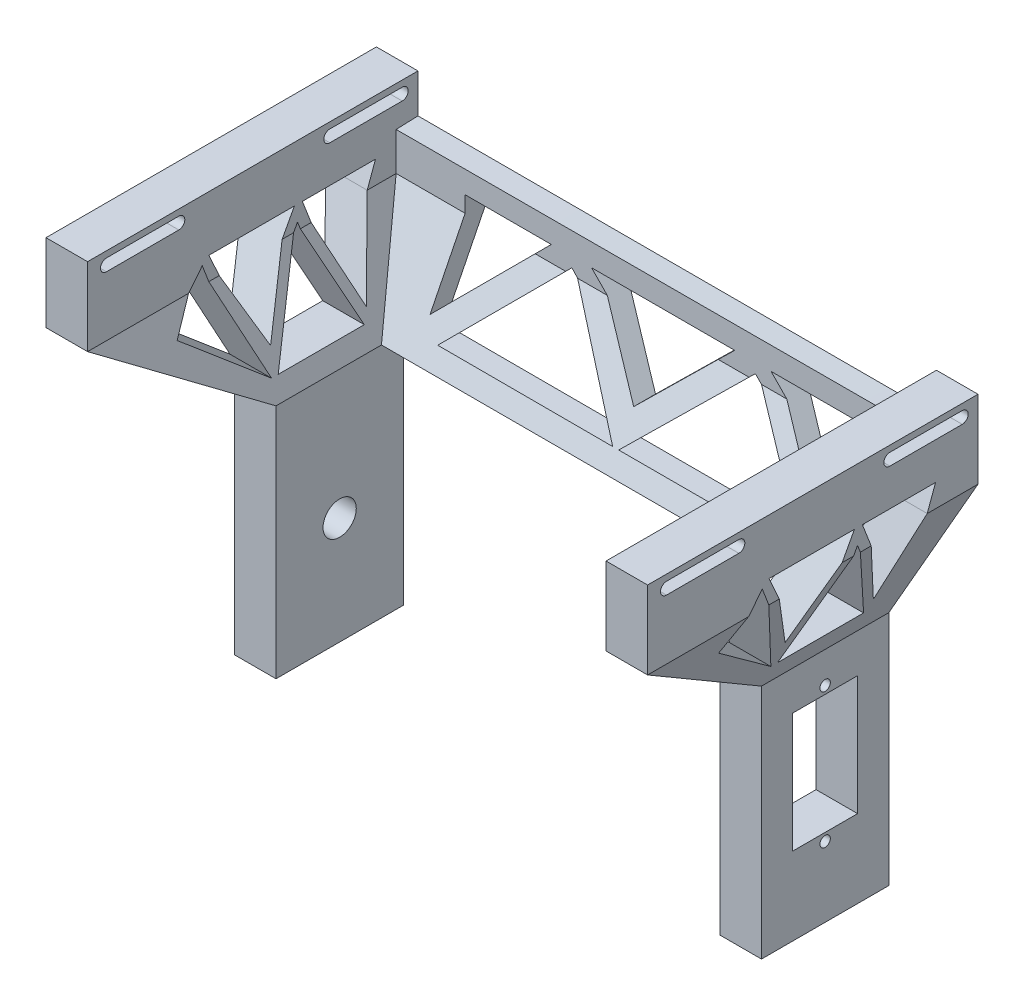
SolidWorks part; units mm, degrees
ref_plane "Plan de face" through (0, 0, 0) normal (0, 0, 1) x (1, 0, 0)
ref_plane "Plan de dessus" through (0, 0, 0) normal (0, 1, 0) x (1, 0, 0)
ref_plane "Plan de droite" through (0, 0, 0) normal (1, 0, 0) x (0, 0, -1)
sketch "Esquisse1" plane through (0, 0, 0) normal (0, 1, 0) x (1, 0, 0)
  line L0 (0, -55) -> (0, 55) construction
  line L1 (-42.725, 12.25) -> (-50.725, 12.25)
  line L2 (-42.725, 12.25) -> (-42.725, -12.25)
  line L3 (-42.725, -12.25) -> (-50.725, -12.25)
  line L4 (-50.725, 12.25) -> (-50.725, -12.25)
  line L5 (-42.725, 12.25) -> (-50.725, -12.25) construction
  line L6 (-42.725, -12.25) -> (-50.725, 12.25) construction
  line L7 (42.725, -12.25) -> (50.725, -12.25)
  line L8 (50.725, 12.25) -> (50.725, -12.25)
  line L9 (42.725, 12.25) -> (50.725, 12.25)
  line L10 (42.725, 12.25) -> (42.725, -12.25)
  line L11 (0, 0) -> (1.1926, 0) construction
  point P0 (-46.725, 0)
  dimension "D1" = 8
  dimension "D2" = 24.5
  dimension "D3" = 42.725
  dimension "D4" = 0
extrude "Boss.-Extru.1" add sketch "Esquisse1" along normal blind 40.5 and the other way blind 5
sketch "Esquisse3" plane through (-50.725, 0, 0) normal (-1, 0, 0) x (0, 0, 1)
  line L0 (-12.25, -5) -> (12.25, -5) construction
  line L2 (-12.25, 40.5) -> (-12.25, -5) construction
  circle A0 centre (0, 15.67) radius 3.2
  dimension "D1" = 20.67
  dimension "D2" = 12.25
extrude "Enlèv. mat.-Extru.1" cut sketch "Esquisse3" against normal blind 10.5
sketch "Esquisse4" plane through (50.725, 0, 0) normal (1, 0, 0) x (0, 0, -1)
  line L0 (-12.25, -5) -> (12.25, -5) construction
  line L1 (-6.25, 33) -> (6.25, 33)
  line L2 (-6.25, 33) -> (-6.25, 10)
  line L3 (-6.25, 10) -> (6.25, 10)
  line L4 (6.25, 33) -> (6.25, 10)
  line L6 (-12.25, 40.5) -> (-12.25, -5) construction
  dimension "D1" = 12.5
  dimension "D2" = 23
  dimension "D3" = 15
  dimension "D4" = 6
extrude "Enlèv. mat.-Extru.2" cut sketch "Esquisse4" against normal blind 10.5
ref_plane "Plan1" through (0, 60.5, 0) normal (0, 1, 0) x (1, 0, 0)
sketch "Esquisse5" plane through (0, 60.5, 0) normal (0, 1, 0) x (1, 0, 0)
  line L7 (-42.725, 12.25) -> (-50.725, 12.25) construction
  line L8 (-57.9, 22.25) -> (-49.9, 22.25)
  line L9 (-57.9, 22.25) -> (-57.9, -41.35)
  line L10 (-57.9, -41.35) -> (-49.9, -41.35)
  line L11 (-49.9, 22.25) -> (-49.9, -41.35)
  line L12 (0, -55) -> (0, 55) construction
  line L13 (57.9, -41.35) -> (49.9, -41.35)
  line L14 (49.9, 22.25) -> (49.9, -41.35)
  line L15 (57.9, 22.25) -> (49.9, 22.25)
  line L16 (57.9, 22.25) -> (57.9, -41.35)
  point P5 (0, 0)
  dimension "D2" = 8
  dimension "D3" = 63.6
  dimension "D4" = 10
  dimension "D5" = 115.8
extrude "Boss.-Extru.2" add sketch "Esquisse5" along normal blind 15 separate body
sketch "Esquisse6" plane through (-57.9, 0, 0) normal (-1, 0, 0) x (0, 0, 1)
  line L0 (-19.2156, 73.15) -> (-5.2844, 73.15) construction
  line L1 (-19.2156, 74.3) -> (-5.2844, 74.3)
  line L2 (-19.2156, 72) -> (-5.2844, 72)
  line L4 (-22.25, 75.5) -> (-22.25, 60.5) construction
  line L5 (23.7844, 73.15) -> (37.7156, 73.15) construction
  line L6 (23.7844, 74.3) -> (37.7156, 74.3)
  line L7 (23.7844, 72) -> (37.7156, 72)
  line L8 (-22.25, 68) -> (41.35, 68) construction
  line L9 (41.35, 75.5) -> (41.35, 60.5) construction
  arc A0 (-19.2156, 74.3) -> (-19.2156, 72) centre (-19.2156, 73.15) ccw
  arc A1 (-5.2844, 72) -> (-5.2844, 74.3) centre (-5.2844, 73.15) ccw
  arc A2 (23.7844, 74.3) -> (23.7844, 72) centre (23.7844, 73.15) ccw
  arc A3 (37.7156, 72) -> (37.7156, 74.3) centre (37.7156, 73.15) ccw
  point P2 (-12.25, 73.15)
  point P15 (30.75, 73.15)
  dimension "D4" = 5.15
  dimension "D3" = 2
extrude "Enlèv. mat.-Extru.3" cut sketch "Esquisse6" against normal through all
loft "Lissage1" add section face at (53.9, 60.5, 9.55) section face at (46.725, 40.5, 0)
loft "Lissage2" add section face at (-53.9, 60.5, 9.55) section face at (-46.725, 40.5, 0)
sketch "Esquisse14" plane through (42.725, 0, 0) normal (-1, 0, 0) x (0, 0, 1)
  line L0 (0, 36.6139) -> (0, 6.0449) construction
  line L1 (0, 33.5) -> (0.6284, 33.5) construction
  line L2 (6.25, 33) -> (-6.25, 33) construction
  line L3 (6.25, 21.5) -> (-6.25, 21.5) construction
  line L4 (6.25, 10) -> (6.25, 33) construction
  line L5 (-6.25, 33) -> (-6.25, 10) construction
  circle A0 centre (0, 34.5) radius 1
  circle A1 centre (0, 8.5) radius 1
  dimension "D1" = 0.5
  dimension "D2" = 2
extrude "Enlèv. mat.-Extru.4" cut sketch "Esquisse14" against normal blind 10
sketch "Esquisse17" plane through (24.9806, -8.9618, 0) normal (-0.9413, 0.3377, 0) x (0, 0, 1)
  line L0 (-22.25, 73.7965) -> (-18.05, 73.7965)
  line L1 (-22.25, 73.7965) -> (41.35, 73.7965) construction
  line L2 (-18.05, 73.7965) -> (-8.05, 52.5484)
  line L3 (-12.25, 52.5484) -> (12.25, 52.5484) construction
  line L4 (-8.05, 52.5484) -> (-12.25, 52.5484)
  line L5 (-22.25, 73.7965) -> (-12.25, 52.5484) construction
  line L6 (-12.25, 52.5484) -> (-22.25, 73.7965)
  dimension "D1" = 4.2
  dimension "D2" = 4.2
sketch "Esquisse18" plane through (49.9, 0, 0) normal (-1, 0, 0) x (0, 0, 1)
  line L0 (-18.05, 60.5) -> (-18.05, 68)
  line L1 (-18.05, 68) -> (-22.25, 68)
  line L2 (-22.25, 75.5) -> (-22.25, 60.5) construction
  line L3 (-22.25, 68) -> (-22.25, 60.5)
  line L4 (-22.25, 60.5) -> (-18.05, 60.5)
  dimension "D1" = 7.5
sketch "Esquisse19" plane through (-24.9806, -8.9618, 0) normal (0.9413, 0.3377, 0) x (0, 0, -1)
  line L0 (22.25, 73.7965) -> (18.05, 73.7965)
  line L1 (-41.35, 73.7965) -> (22.25, 73.7965) construction
  line L2 (18.05, 73.7965) -> (8.05, 52.5484)
  line L3 (-12.25, 52.5484) -> (12.25, 52.5484) construction
  line L4 (8.05, 52.5484) -> (12.25, 52.5484)
  line L5 (12.25, 52.5484) -> (22.25, 73.7965)
  dimension "D1" = 4.2
  dimension "D2" = 4.2
sketch "Esquisse20" plane through (-49.9, 0, 0) normal (1, 0, 0) x (0, 0, -1)
  line L0 (18.05, 60.5) -> (18.05, 67.8367)
  line L1 (18.05, 67.8367) -> (22.25, 68)
  line L2 (22.25, 75.5) -> (22.25, 60.5) construction
  line L3 (22.25, 68) -> (22.25, 60.5)
  line L4 (22.25, 60.5) -> (18.05, 60.5)
loft "Lissage3" add profiles "Esquisse18", "Esquisse20"
loft "Lissage4" add profiles "Esquisse19", "Esquisse17"
sketch "Esquisse21" plane through (-57.9, 0, 0) normal (-1, 0, 0) x (0, 0, 1)
  line L0 (-12.415, 41.3844) -> (-8.215, 41.3844) construction
  line L1 (-22.25, 66.1296) -> (-18.05, 66.1296) construction
  line L2 (-22.25, 75.5) -> (-22.25, 60.5) construction
  line L7 (-7.2044, 46.2882) -> (0.0054, 64.8807)
  line L8 (1.5323, 64.8807) -> (10.5, 48.2821)
  line L9 (-12.4781, 60.5) -> (-7.2044, 46.2882)
  line L10 (19.2703, 63.7879) -> (25.8946, 55.5212)
  line L12 (-6.0716, 44.2075) -> (0.9417, 61.895)
  line L13 (0.9417, 61.895) -> (10.5, 44.2075)
  line L14 (17.9813, 64.8807) -> (10.5, 48.2821)
  line L15 (25.8946, 55.5212) -> (26.9774, 56.3888)
  line L16 (26.9774, 56.3888) -> (21.0001, 64.8807)
  line L17 (-6.0716, 44.2075) -> (10.5, 44.2075)
  line L18 (-7.2044, 46.2882) -> (0.0054, 64.8807)
  line L19 (-6.5312, 44.2075) -> (-6.0716, 44.2075)
  line L20 (10.5, 48.2821) -> (17.9813, 64.8807)
  line L21 (-1.6933, 60.5) -> (-12.4781, 60.5)
  line L22 (19.2703, 63.7879) -> (25.8946, 55.5212)
  line L23 (11.7759, 44.2075) -> (19.2703, 63.7879)
  line L24 (-14.0771, 64.8807) -> (-16.2816, 64.8807)
  line L25 (21.0001, 64.8807) -> (26.9774, 56.3888)
  line L26 (-22.25, 60.5) -> (41.35, 60.5) construction
  line L27 (-12.4781, 60.5) -> (-14.0771, 64.8807)
  line L28 (0.0054, 64.8807) -> (-1.6933, 60.5)
  line L29 (1.5323, 64.8807) -> (17.9813, 64.8807)
  line L30 (16.0068, 60.5) -> (3.899, 60.5)
  line L31 (3.899, 60.5) -> (1.5323, 64.8807)
  line L32 (18.0119, 60.5) -> (19.2703, 63.7879)
  line L33 (21.905, 60.5) -> (18.0119, 60.5)
  line L34 (-16.2816, 64.8807) -> (-8.215, 44.2075)
  line L35 (-8.215, 44.2075) -> (-6.0716, 44.2075)
  line L36 (21.0001, 64.8807) -> (23.9888, 60.6348)
  line L37 (-14.0771, 64.8807) -> (0.0054, 64.8807)
  line L38 (-12.4781, 60.5) -> (-1.6933, 60.5)
  line L39 (0.0054, 64.8807) -> (-14.0771, 64.8807)
  line L40 (0.0054, 64.8807) -> (1.5323, 64.8807)
  line L41 (10.5, 44.2075) -> (11.7759, 44.2075)
  line L42 (17.9813, 64.8807) -> (21.0001, 64.8807)
  line L43 (11.7759, 44.2075) -> (25.8946, 55.5212)
  dimension "D1" = 4.2
  dimension "D2" = 4.2
extrude "Enlèv. mat.-Extru.9" cut sketch "Esquisse21" against normal blind 150
sketch "Esquisse22" plane through (0, 0, -18.05) normal (0, 0, 1) x (1, 0, 0)
  line L0 (-36.6242, 47.0126) -> (-36.6242, 63.5978)
  line L1 (-36.6242, 63.5978) -> (38.9783, 63.5978)
  line L4 (-36.6242, 47.0126) -> (-33.6917, 44.08)
  line L5 (-33.6917, 44.08) -> (-16.0678, 61.7039)
  line L6 (-16.0678, 61.7039) -> (1.1608, 44.0476)
  line L7 (1.1608, 44.0476) -> (19.2554, 61.7039)
  line L8 (19.2554, 61.7039) -> (36.484, 44.0476)
  line L9 (36.484, 44.0476) -> (38.9783, 46.4814)
  line L10 (38.9783, 46.4814) -> (22.2765, 63.5978)
  line L11 (22.2765, 63.5978) -> (15.2736, 63.5978)
  line L12 (15.2736, 63.5978) -> (1.1608, 49.8268)
  line L13 (1.1608, 49.8268) -> (-12.2766, 63.5978)
  line L14 (-12.2766, 63.5978) -> (-20.039, 63.5978)
  line L15 (-20.039, 63.5978) -> (-36.6242, 47.0126)
  line L16 (-33.6917, 44.08) -> (1.1608, 44.0476)
  line L17 (-16.0678, 61.7039) -> (-33.6917, 44.08)
  line L18 (-12.2766, 63.5978) -> (15.2736, 63.5978)
  line L19 (1.1608, 49.8268) -> (-12.2766, 63.5978)
  line L20 (22.2765, 63.5978) -> (38.9783, 63.5978)
  line L21 (38.9783, 46.4814) -> (22.2765, 63.5978)
  line L22 (38.9783, 46.4814) -> (38.9783, 63.5978)
  line L23 (1.1608, 44.0476) -> (36.484, 44.0476)
  line L24 (19.2554, 61.7039) -> (1.1608, 44.0476)
sketch "Esquisse23" plane through (0, 0, -18.05) normal (0, 0, 1) x (1, 0, 0)
  line L0 (22.2765, 63.5978) -> (38.9783, 63.5978)
  line L1 (38.9783, 63.5978) -> (38.9783, 46.4814)
  line L2 (38.9783, 46.4814) -> (22.2765, 63.5978)
  line L3 (19.2554, 61.7039) -> (1.1608, 44.0476)
  line L4 (1.1608, 44.0476) -> (36.484, 44.0476)
  line L5 (36.484, 44.0476) -> (19.2554, 61.7039)
  line L6 (-12.2766, 63.5978) -> (15.2736, 63.5978)
  line L7 (15.2736, 63.5978) -> (1.1608, 49.8268)
  line L8 (1.1608, 49.8268) -> (-12.2766, 63.5978)
  line L9 (-33.6917, 44.08) -> (-16.0678, 61.7039)
  line L10 (-16.0678, 61.7039) -> (0, 44.0487)
  line L11 (-33.6917, 44.08) -> (1.1608, 44.0476) construction
  line L12 (0, 44.0487) -> (-33.6917, 44.08)
  line L13 (-36.6242, 47.0126) -> (-20.039, 63.5978)
  line L14 (-20.039, 63.5978) -> (-36.6242, 63.5978)
  line L15 (-36.6242, 63.5978) -> (-36.6242, 47.0126)
extrude "Enlèv. mat.-Extru.13" cut sketch "Esquisse23" against normal blind 20 and the other way blind 20 contours L15 L13 L14 | L12 L9 L10 | L8 L6 L7 | L2 L0 L1 | L5 L3 L4
